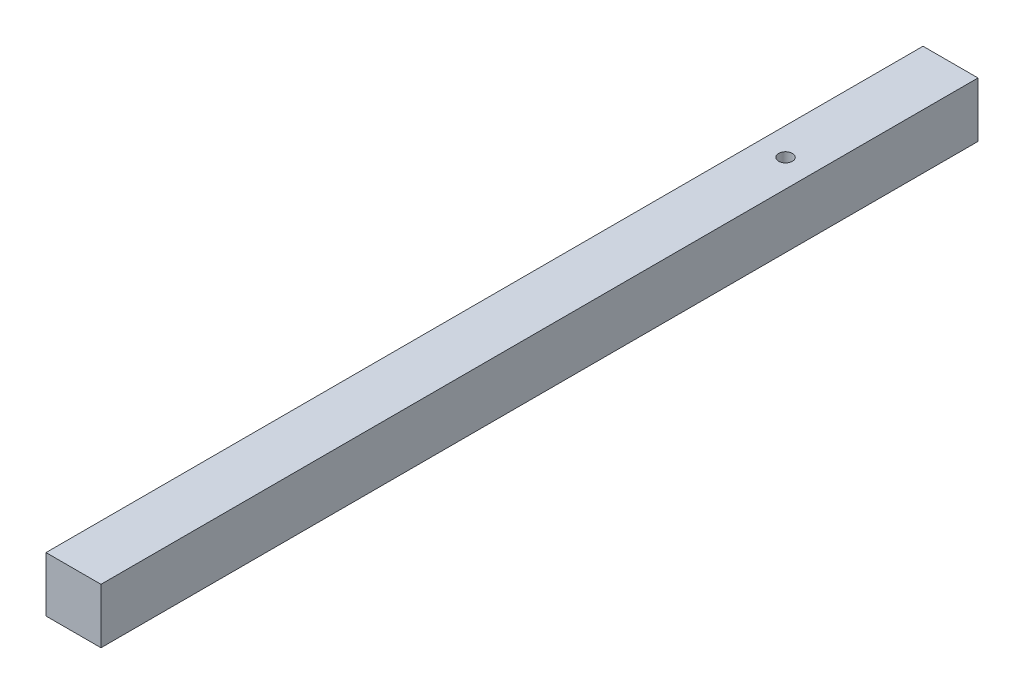
SolidWorks part; units mm, degrees
ref_plane "前视基准面" through (0, 0, 0) normal (0, 0, 1) x (1, 0, 0)
ref_plane "上视基准面" through (0, 0, 0) normal (0, 1, 0) x (1, 0, 0)
ref_plane "右视基准面" through (0, 0, 0) normal (1, 0, 0) x (0, 0, -1)
other "Configuration Table"
sketch "草图1" plane through (0, 0, 0) normal (0, 0, 1) x (1, 0, 0)
  line L1 (0, 0) -> (20, 0)
  line L2 (0, 0) -> (0, 20)
  line L3 (0, 20) -> (20, 20)
  line L4 (20, 0) -> (20, 20)
  line L5 (0, 0) -> (20, 20) construction
  line L6 (0, 20) -> (20, 0) construction
  point P4 (10, 10)
  dimension "D1" = 20
extrude "凸台-拉伸1" add sketch "草图1" along normal blind 319
sketch "草图2" plane through (0, 20, 0) normal (0, 1, 0) x (1, 0, 0)
  line L0 (10, 0) -> (10, -357.2803) construction
  line L1 (20, 0) -> (0, 0) construction
  circle A0 centre (10, -60) radius 2.5
  dimension "D1" = 5
  dimension "D2" = 60
extrude "切除-拉伸1" cut sketch "草图2" against normal blind 10
